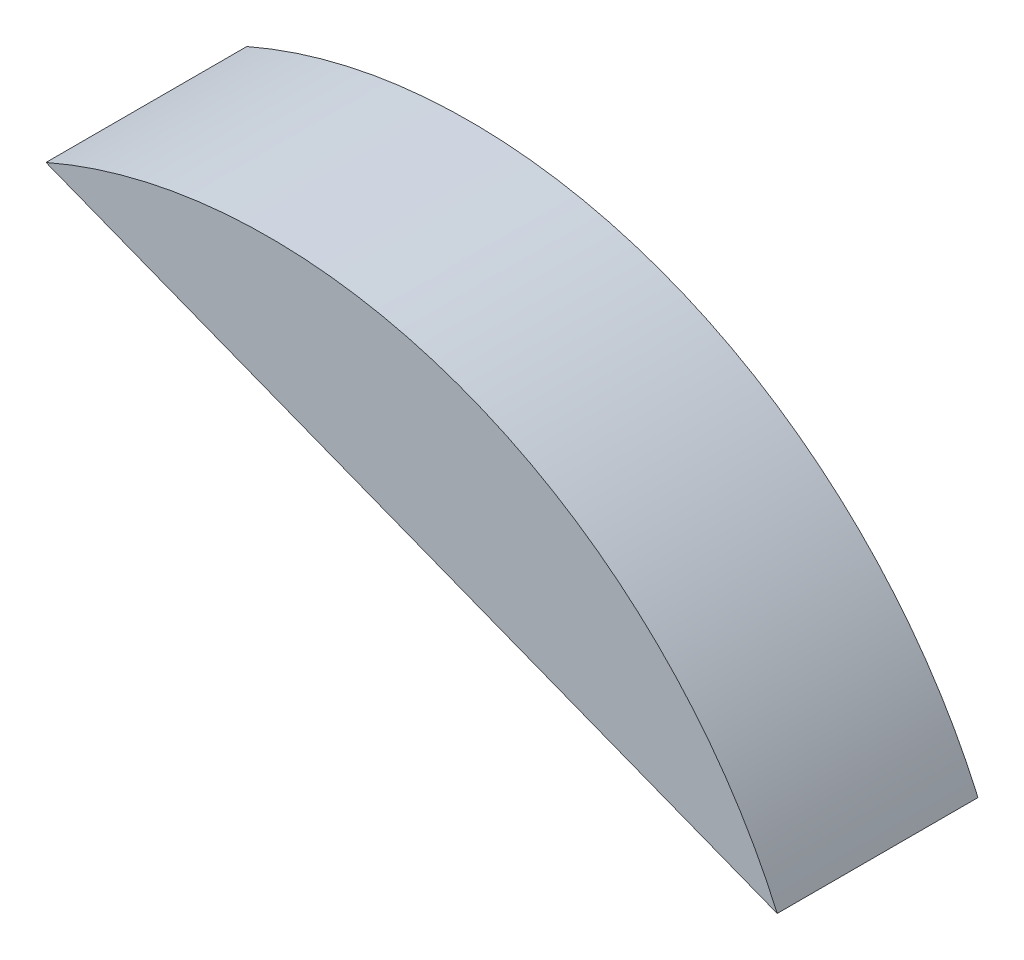
SolidWorks part; units mm, degrees
ref_plane "Front Plane" through (0, 0, 0) normal (0, 0, 1) x (1, 0, 0)
ref_plane "Top Plane" through (0, 0, 0) normal (0, 1, 0) x (1, 0, 0)
ref_plane "Right Plane" through (0, 0, 0) normal (1, 0, 0) x (0, 0, -1)
sketch "CurveSketch" plane through (0, 0, 0) normal (0, 0, 1) x (1, 0, 0)
  line L0 (-13.0738, 31.7833) -> (12.9273, 21.6558)
  arc A0 (12.9273, 21.6558) -> (-13.0738, 31.7833) centre (-5.137, 13.719) ccw
  dimension "D1" = 19.731
extrude "CurveBoss" add sketch "CurveSketch" along normal blind 7.139
